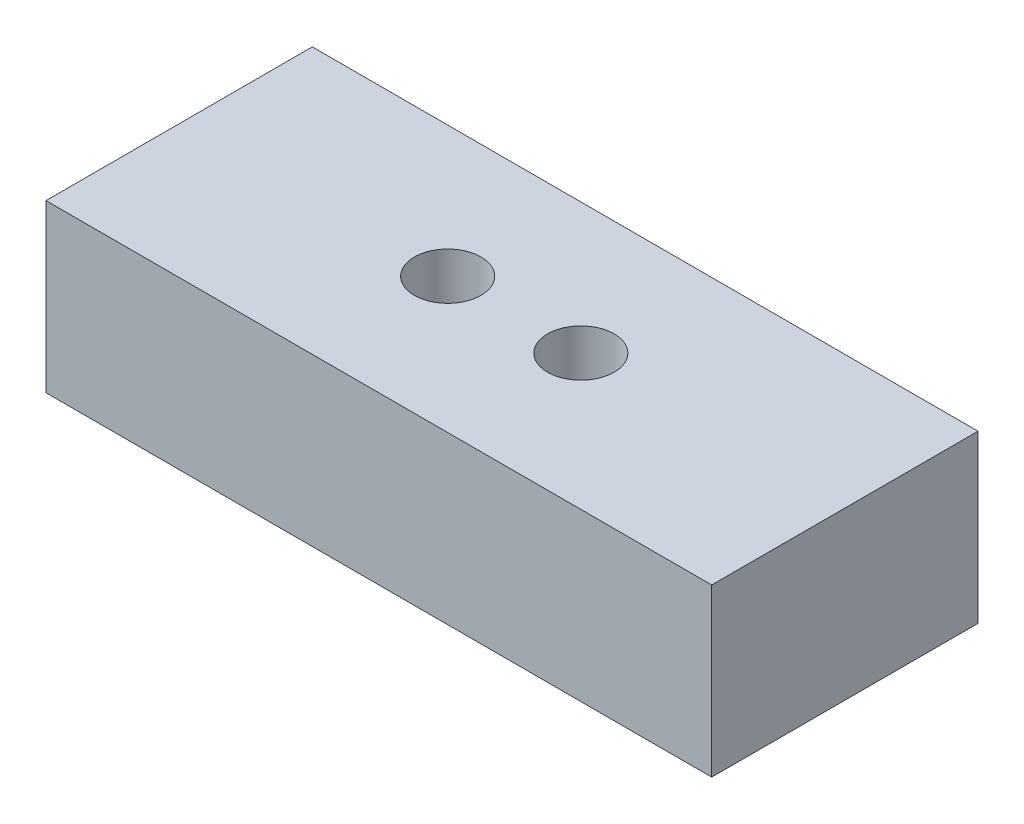
SolidWorks part; units mm, degrees
ref_plane "Front Plane" through (0, 0, 0) normal (0, 0, 1) x (1, 0, 0)
ref_plane "Top Plane" through (0, 0, 0) normal (0, 1, 0) x (1, 0, 0)
ref_plane "Right Plane" through (0, 0, 0) normal (1, 0, 0) x (0, 0, -1)
sketch "Sketch1" plane through (0, 0, 0) normal (0, 1, 0) x (1, 0, 0)
  line L1 (-95.8865, 18.2979) -> (4.1135, 18.2979)
  line L2 (-95.8865, 18.2979) -> (-95.8865, -21.7021)
  line L3 (-95.8865, -21.7021) -> (4.1135, -21.7021)
  line L4 (4.1135, 18.2979) -> (4.1135, -21.7021)
  dimension "D1" = 40
  dimension "D2" = 100
extrude "Boss-Extrude1" add sketch "Sketch1" along normal blind 25
sketch "Sketch2" plane through (0, 25, 0) normal (0, 1, 0) x (1, 0, 0)
  line L0 (-95.8865, 18.2979) -> (-95.8865, -21.7021) construction
  line L1 (4.1135, -21.7021) -> (4.1135, 18.2979) construction
  circle A0 centre (-55.8865, -1.3618) radius 5
  circle A1 centre (-35.8865, -1.3618) radius 5
  dimension "D1" = 10
  dimension "D2" = 10
  dimension "D4" = 40
  dimension "D5" = 40
  dimension "D3" = 20
extrude "Cut-Extrude1" cut sketch "Sketch2" against normal blind 10
